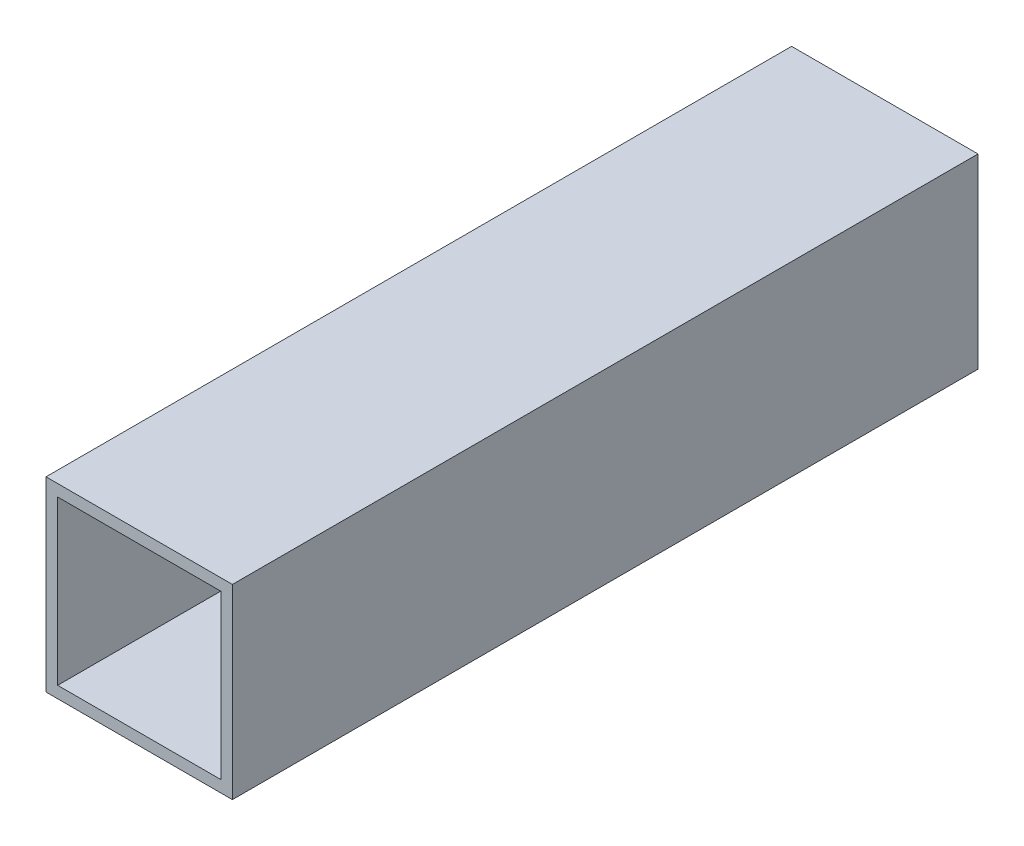
SolidWorks part; units mm, degrees
material "Acrylic (Medium-high impact)"
ref_plane "Front Plane" through (0, 0, 0) normal (0, 0, 1) x (1, 0, 0)
ref_plane "Top Plane" through (0, 0, 0) normal (0, 1, 0) x (1, 0, 0)
ref_plane "Right Plane" through (0, 0, 0) normal (1, 0, 0) x (0, 0, -1)
sketch "Sketch1" plane through (0, 0, 0) normal (0, 0, 1) x (1, 0, 0)
  line L1 (12.7, 12.7) -> (-12.7, 12.7)
  line L2 (12.7, 12.7) -> (12.7, -12.7)
  line L3 (12.7, -12.7) -> (-12.7, -12.7)
  line L4 (-12.7, 12.7) -> (-12.7, -12.7)
  line L5 (12.7, 12.7) -> (-12.7, -12.7) construction
  line L6 (12.7, -12.7) -> (-12.7, 12.7) construction
  line L7 (11.1125, 11.1125) -> (-11.1125, 11.1125)
  line L8 (11.1125, 11.1125) -> (11.1125, -11.1125)
  line L9 (11.1125, -11.1125) -> (-11.1125, -11.1125)
  line L10 (-11.1125, 11.1125) -> (-11.1125, -11.1125)
  line L11 (11.1125, 11.1125) -> (-11.1125, -11.1125) construction
  line L12 (11.1125, -11.1125) -> (-11.1125, 11.1125) construction
  point P0 (0, 0)
  point P6 (0, 0)
  dimension "D1" = 25.4
  dimension "D2" = 1.5875
extrude "Boss-Extrude1" add sketch "Sketch1" along normal blind 101.6
